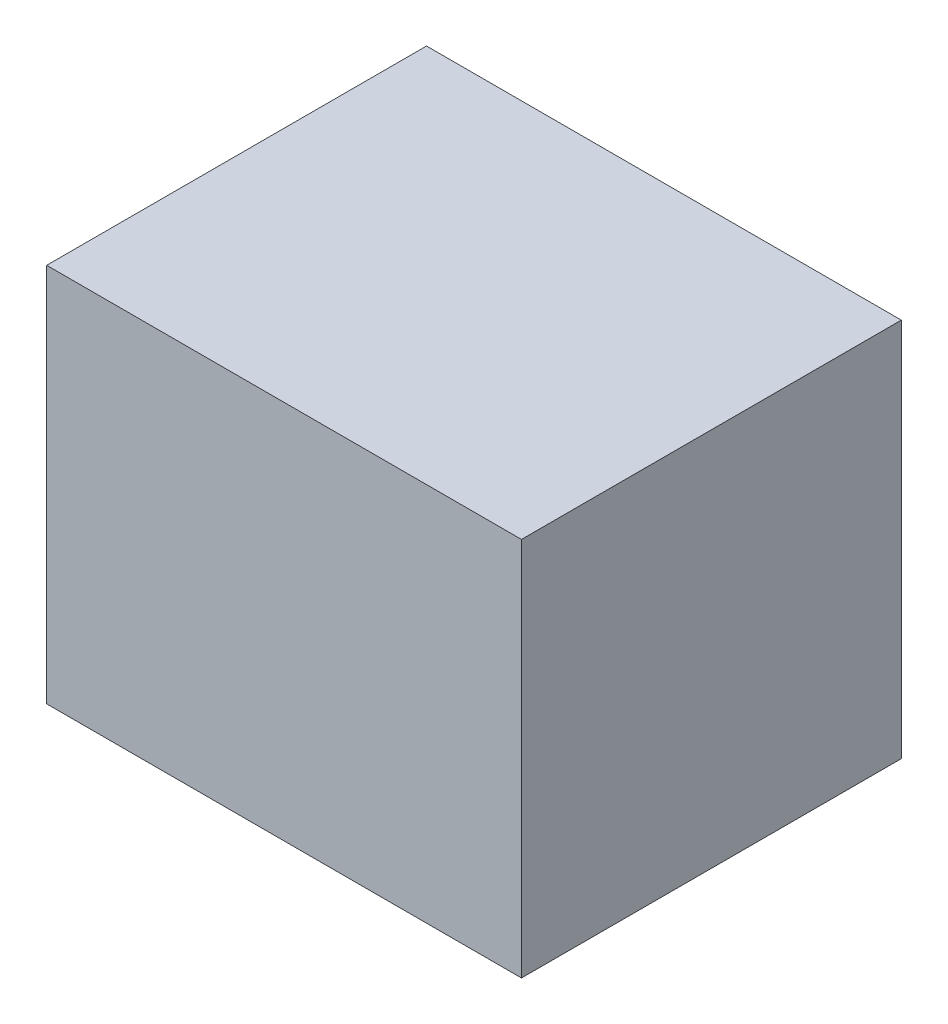
SolidWorks part; units mm, degrees
ref_plane "Front Plane" through (0, 0, 0) normal (0, 0, 1) x (1, 0, 0)
ref_plane "Top Plane" through (0, 0, 0) normal (0, 1, 0) x (1, 0, 0)
ref_plane "Right Plane" through (0, 0, 0) normal (1, 0, 0) x (0, 0, -1)
sketch "Sketch1" plane through (0, 0, 0) normal (1, 0, 0) x (0, 0, -1)
  line L1 (-50.8, 50.8) -> (50.8, 50.8)
  line L2 (-50.8, 50.8) -> (-50.8, -50.8)
  line L3 (-50.8, -50.8) -> (50.8, -50.8)
  line L4 (50.8, 50.8) -> (50.8, -50.8)
  line L5 (-50.8, 50.8) -> (50.8, -50.8) construction
  line L6 (-50.8, -50.8) -> (50.8, 50.8) construction
  point P0 (0, 0)
  dimension "D1" = 101.6
  dimension "D2" = 101.6
extrude "Boss-Extrude1" add sketch "Sketch1" along normal blind 127 contours L4 L3 L2 L1
